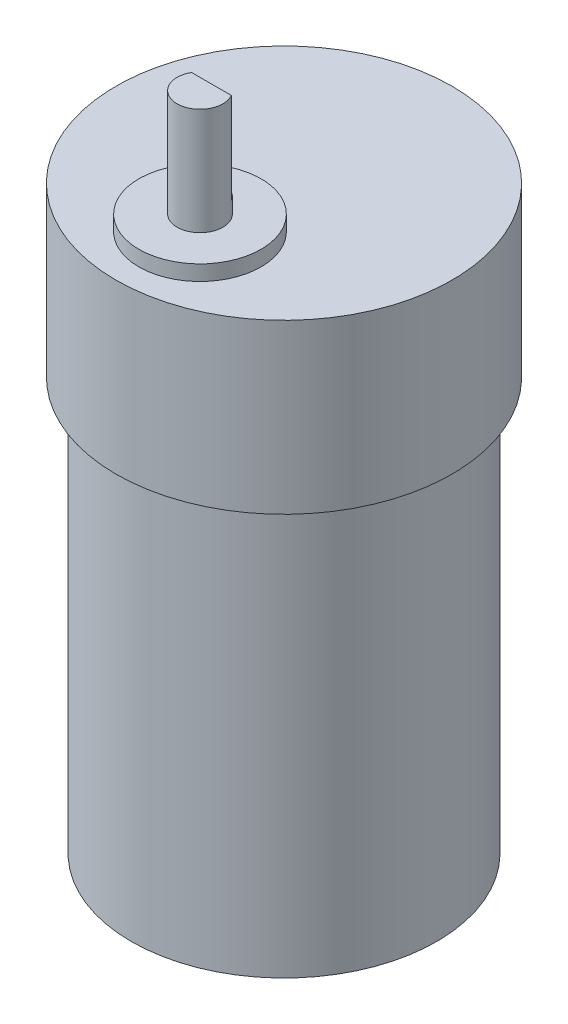
SolidWorks part; units mm, degrees
ref_plane "Front Plane" through (0, 0, 0) normal (0, 0, 1) x (1, 0, 0)
ref_plane "Top Plane" through (0, 0, 0) normal (0, 1, 0) x (1, 0, 0)
ref_plane "Right Plane" through (0, 0, 0) normal (1, 0, 0) x (0, 0, -1)
sketch "Sketch1" plane through (0, 0, 0) normal (0, 1, 0) x (1, 0, 0)
  circle A0 centre (0, 0) radius 15.875
  dimension "D1" = 31.75
extrude "Boss-Extrude1" add sketch "Sketch1" along normal blind 42.8625
sketch "Sketch2" plane through (0, 42.8625, 0) normal (0, 1, 0) x (1, 0, 0)
  circle A0 centre (0, 0) radius 17.4625
  dimension "D1" = 34.925
extrude "Boss-Extrude2" add sketch "Sketch2" along normal blind 17.4625
sketch "Sketch3" plane through (0, 60.325, 0) normal (0, 1, 0) x (1, 0, 0)
  circle A0 centre (0, -8.7325) radius 6.35
  dimension "D1" = 12.7
  dimension "D2" = 8.7325
extrude "Boss-Extrude3" add sketch "Sketch3" along normal blind 1.5875
sketch "Sketch4" plane through (0, 61.9125, 0) normal (0, 1, 0) x (1, 0, 0)
  circle A0 centre (0, -8.7325) radius 2.3813
  dimension "D1" = 4.7625
extrude "Boss-Extrude4" add sketch "Sketch4" along normal blind 11.1125
sketch "Sketch5" plane through (0, 73.025, 0) normal (0, 1, 0) x (1, 0, 0)
  line L0 (-2.0622, -7.5419) -> (2.0622, -7.5419)
  line L1 (0, -8.7325) -> (0, -6.3513) construction
  circle A0 centre (0, -8.7325) radius 2.3812 construction
  arc A1 (2.0622, -7.5419) -> (-2.0622, -7.5419) centre (0, -8.7325) ccw
  point P5 (0, -7.5419)
  point P8 (0, -7.5419)
extrude "Cut-Extrude1" cut sketch "Sketch5" against normal blind 9.525
sketch "Sketch6" plane through (0, 0, 0) normal (0, -1, 0) x (1, 0, 0)
  circle A0 centre (0, 0) radius 4.7625
  dimension "D1" = 9.525
extrude "Boss-Extrude5" add sketch "Sketch6" along normal blind 1.5875
